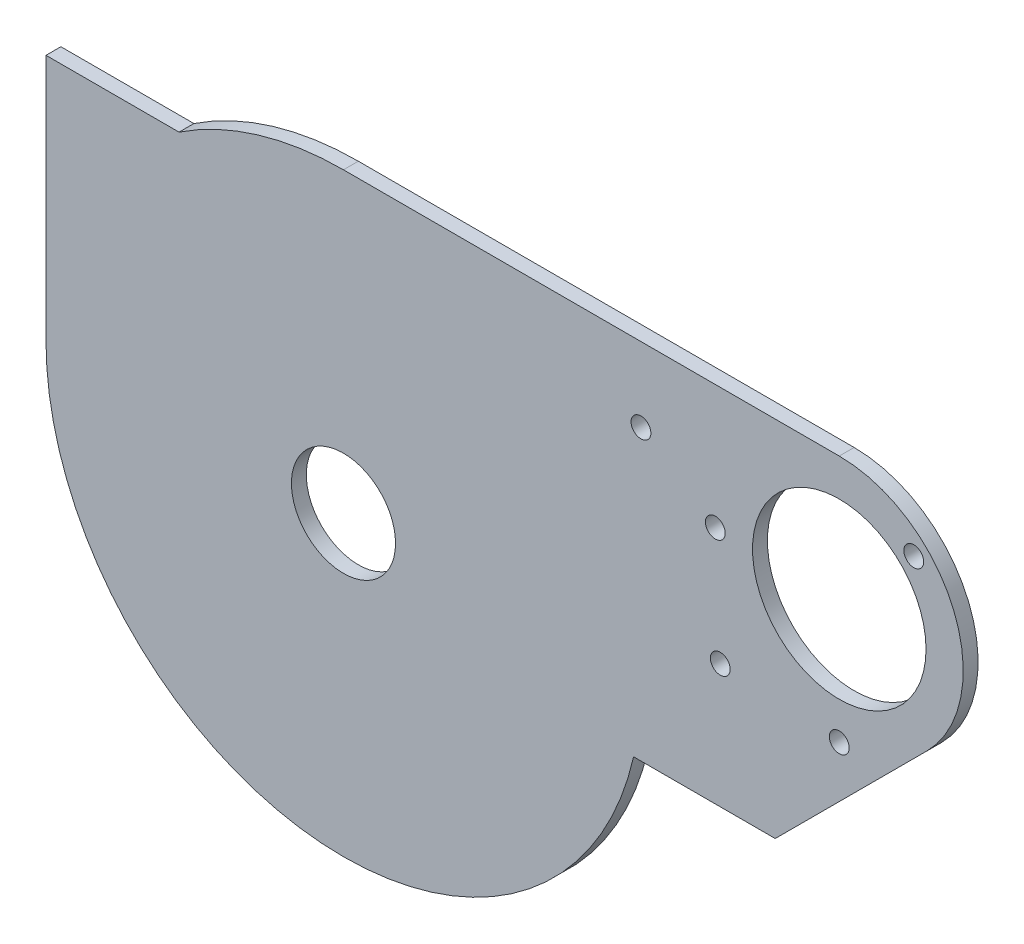
SolidWorks part; units mm, degrees
ref_plane "前视基准面" through (0, 0, 0) normal (0, 0, 1) x (1, 0, 0)
ref_plane "上视基准面" through (0, 0, 0) normal (0, 1, 0) x (1, 0, 0)
ref_plane "右视基准面" through (0, 0, 0) normal (1, 0, 0) x (0, 0, -1)
sketch "Sketch1" plane through (0, 0, 0) normal (0, 0, 1) x (1, 0, 0)
  line L0 (-10.9179, 60) -> (113.3582, 60) construction
  line L3 (-33.1662, 50) -> (-60, 50)
  line L4 (-60, 0) -> (-60, 50)
  line L6 (67.51, -32.8453) -> (81.2655, -19.0899) construction
  line L7 (81.2655, -19.0899) -> (117.6777, 17.3223)
  line L12 (58.5132, -13.2742) -> (87.0811, -13.2742)
  line L13 (0, 60) -> (100, 60)
  arc A0 (0, 60) -> (58.5132, -13.2742) centre (0, 0) ccw
  circle A2 centre (0, 0) radius 10.5
  arc A8 (117.6777, 17.3223) -> (100, 60) centre (100, 35) ccw
  circle A9 centre (100, 35) radius 17.5
  dimension "D1" = 120
  dimension "D3" = 21
  dimension "D5" = 50
  dimension "D4" = 100
  dimension "D6" = 35
extrude "Boss-Extrude1" add sketch "Sketch1" along normal blind 3
sketch "Sketch2" plane through (0, 0, 3) normal (0, 0, 1) x (1, 0, 0)
  line L1 (-60, 0) -> (-60, 50) construction
  line L2 (0, 60) -> (100, 60) construction
  line L3 (58.5132, -13.2742) -> (87.0811, -13.2742) construction
  circle A1 centre (0, 0) radius 57
  circle A2 centre (60, 45) radius 2
  circle A3 centre (76, 11.7258) radius 2
  circle A6 centre (100, 35) radius 14
  dimension "D1" = 15
  dimension "D4" = 136
  dimension "D5" = 28
  dimension "D2" = 120
  dimension "D3" = 25
extrude "Cut-Extrude1" cut sketch "Sketch2" against normal up to next contours A2 | A3
sketch "Sketch3" plane through (0, 0, 3) normal (0, 0, 1) x (1, 0, 0)
  line L0 (117.6777, 52.6777) -> (112.3744, 47.3744) construction
  circle A0 centre (100, 35) radius 17.5 construction
  circle A1 centre (100, 35) radius 25 construction
  circle A2 centre (100, 10) radius 2
  circle A3 centre (75, 35) radius 2
  circle A4 centre (115.026, 50.026) radius 2
  dimension "D1" = 35
extrude "Cut-Extrude2" cut sketch "Sketch3" against normal up to next
